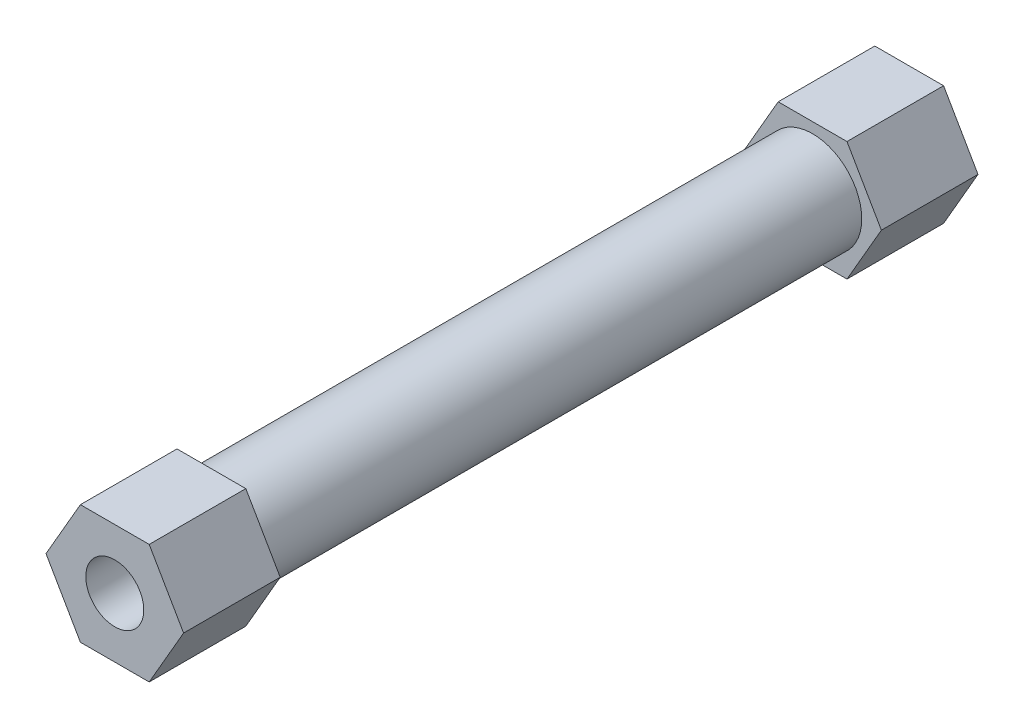
SolidWorks part; units mm, degrees
ref_plane "Ön Düzlem" through (0, 0, 0) normal (0, 0, 1) x (1, 0, 0)
ref_plane "Üst Düzlem" through (0, 0, 0) normal (0, 1, 0) x (1, 0, 0)
ref_plane "Sağ Düzlem" through (0, 0, 0) normal (1, 0, 0) x (0, 0, -1)
sketch "Çizim1" plane through (0, 0, 0) normal (0, 0, 1) x (1, 0, 0)
  line L1 (1.6021, -2.775) -> (3.2043, 0)
  line L2 (3.2043, 0) -> (1.6021, 2.775)
  line L3 (1.6021, 2.775) -> (-1.6021, 2.775)
  line L4 (-1.6021, 2.775) -> (-3.2043, 0)
  line L5 (-3.2043, 0) -> (-1.6021, -2.775)
  line L6 (-1.6021, -2.775) -> (1.6021, -2.775)
  circle A0 centre (0, 0) radius 2.775 construction
  dimension "D1" = 5.55
extrude "Yükseklik-Ekstrüzyon1" add sketch "Çizim1" along normal blind 37
sketch "Çizim2" plane through (0, 0, 37) normal (0, 0, 1) x (1, 0, 0)
  circle A0 centre (0, 0) radius 2.29
  circle A1 centre (0, 0) radius 3.29
  dimension "D1" = 4.58
  dimension "D2" = 1
extrude "Kes-Ekstrüzyon1" cut sketch "Çizim2" against normal blind 28 from offset 4.5 offset against normal yes
sketch "Çizim3" plane through (0, 0, 0) normal (0, 0, -1) x (-1, 0, 0)
  circle A0 centre (0, 0) radius 1.35
  dimension "D1" = 2.7
extrude "Kes-Ekstrüzyon2" cut sketch "Çizim3" against normal through all
